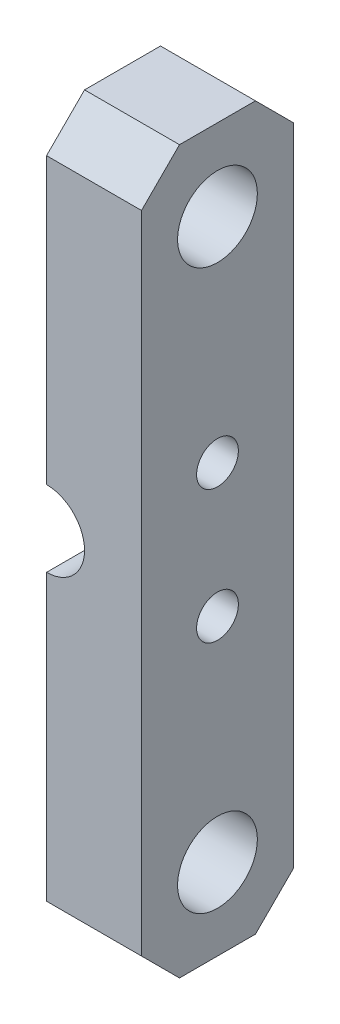
SolidWorks part; units mm, degrees
ref_plane "Front Plane" through (0, 0, 0) normal (0, 0, 1) x (1, 0, 0)
ref_plane "Top Plane" through (0, 0, 0) normal (0, 1, 0) x (1, 0, 0)
ref_plane "Right Plane" through (0, 0, 0) normal (1, 0, 0) x (0, 0, -1)
ref_plane "Plane1" through (10, 0, 0) normal (1, 0, 0) x (0, 0, -1)
sketch "Sketch1" plane through (10, 0, 0) normal (1, 0, 0) x (0, 0, -1)
  line L0 (18, -38) -> (18, 38)
  line L1 (18, 38) -> (2, 38)
  line L2 (2, 38) -> (2, -38)
  line L3 (2, -38) -> (18, -38)
extrude "Boss-Extrude1" add sketch "Sketch1" against normal blind 10
hole_wizard "Hole1" positions "Sketch3" profile "Sketch2" legacy
sketch "Sketch3" plane through (10, 0, 0) normal (1, 0, 0) x (0, 0, -1)
  point P0 (10, -7)
sketch "Sketch2" plane through (10, -7, -10) normal (0, 1, 0) x (0, 0, -1)
  line L0 (0, 0) -> (0, 10)
  line L1 (0, 10) -> (2.2, 10)
  line L2 (2.2, 10) -> (2.2, 0)
  line L3 (2.2, 0) -> (0, 0)
  line L4 (0, 110) -> (0, -10) construction
  dimension "Diameter" = 4.4
  dimension "Depth" = 10
hole_wizard "Hole2" positions "Sketch5" profile "Sketch4" legacy
sketch "Sketch5" plane through (10, 0, 0) normal (1, 0, 0) x (0, 0, -1)
  point P0 (10, 7)
sketch "Sketch4" plane through (10, 7, -10) normal (0, 1, 0) x (0, 0, -1)
  line L0 (0, 0) -> (0, 10)
  line L1 (0, 10) -> (2.2, 10)
  line L2 (2.2, 10) -> (2.2, 0)
  line L3 (2.2, 0) -> (0, 0)
  line L4 (0, 110) -> (0, -10) construction
  dimension "Diameter" = 4.4
  dimension "Depth" = 10
hole_wizard "Hole3" positions "Sketch7" profile "Sketch6" legacy
sketch "Sketch7" plane through (10, 0, 0) normal (1, 0, 0) x (0, 0, -1)
  point P0 (10, -29.4449)
sketch "Sketch6" plane through (10, -29.4449, -10) normal (0, 1, 0) x (0, 0, -1)
  line L0 (0, 0) -> (0, 10)
  line L1 (0, 10) -> (4.2, 10)
  line L2 (4.2, 10) -> (4.2, 0)
  line L3 (4.2, 0) -> (0, 0)
  line L4 (0, 110) -> (0, -10) construction
  dimension "Diameter" = 8.4
  dimension "Depth" = 10
hole_wizard "Hole4" positions "Sketch9" profile "Sketch8" legacy
sketch "Sketch9" plane through (10, 0, 0) normal (1, 0, 0) x (0, 0, -1)
  point P0 (10, 29.4449)
sketch "Sketch8" plane through (10, 29.4449, -10) normal (0, 1, 0) x (0, 0, -1)
  line L0 (0, 0) -> (0, 10)
  line L1 (0, 10) -> (4.2, 10)
  line L2 (4.2, 10) -> (4.2, 0)
  line L3 (4.2, 0) -> (0, 0)
  line L4 (0, 110) -> (0, -10) construction
  dimension "Diameter" = 8.4
  dimension "Depth" = 10
hole_wizard "Hole5" positions "Sketch11" profile "Sketch10" legacy
sketch "Sketch11" plane through (0, 0, -2) normal (0, 0, 1) x (1, 0, 0)
  point P0 (0, 0)
sketch "Sketch10" plane through (0, 0, -2) normal (1, 0, 0) x (0, -1, 0)
  line L0 (0, 0) -> (0, 16)
  line L1 (0, 16) -> (4, 16)
  line L2 (4, 16) -> (4, 0)
  line L3 (4, 0) -> (0, 0)
  line L4 (0, 110) -> (0, -10) construction
  dimension "Diameter" = 8
  dimension "Depth" = 16
chamfer "Chamfer1" distance 4 angle 45 1 edges at (5, 38, -2)
chamfer "Chamfer2" distance 4 angle 45 1 edges at (5, 38, -18)
chamfer "Chamfer3" distance 4 angle 45 1 edges at (5, -38, -18)
chamfer "Chamfer4" distance 4 angle 45 1 edges at (5, -38, -2)
